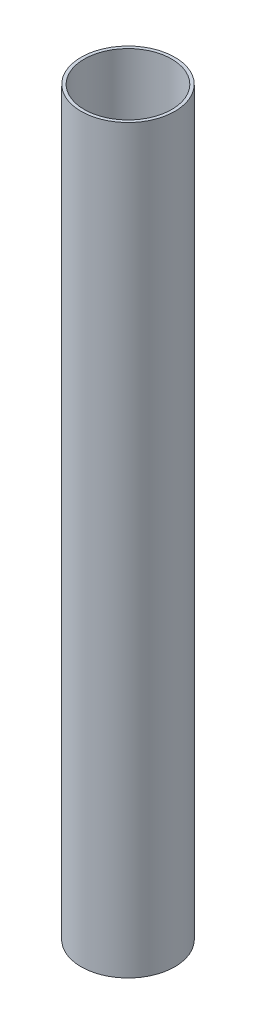
SolidWorks part; units mm, degrees
material "Acrylic (Medium-high impact)"
ref_plane "Front Plane" through (0, 0, 0) normal (0, 0, 1) x (1, 0, 0)
ref_plane "Top Plane" through (0, 0, 0) normal (0, 1, 0) x (1, 0, 0)
ref_plane "Right Plane" through (0, 0, 0) normal (1, 0, 0) x (0, 0, -1)
sketch "Sketch1" plane through (0, 0, 0) normal (0, 1, 0) x (1, 0, 0)
  circle A0 centre (0, 0) radius 22.5
  circle A1 centre (0, 0) radius 21
  dimension "D1" = 42
  dimension "D2" = 45
extrude "Boss-Extrude1" add sketch "Sketch1" along normal blind 355.6
